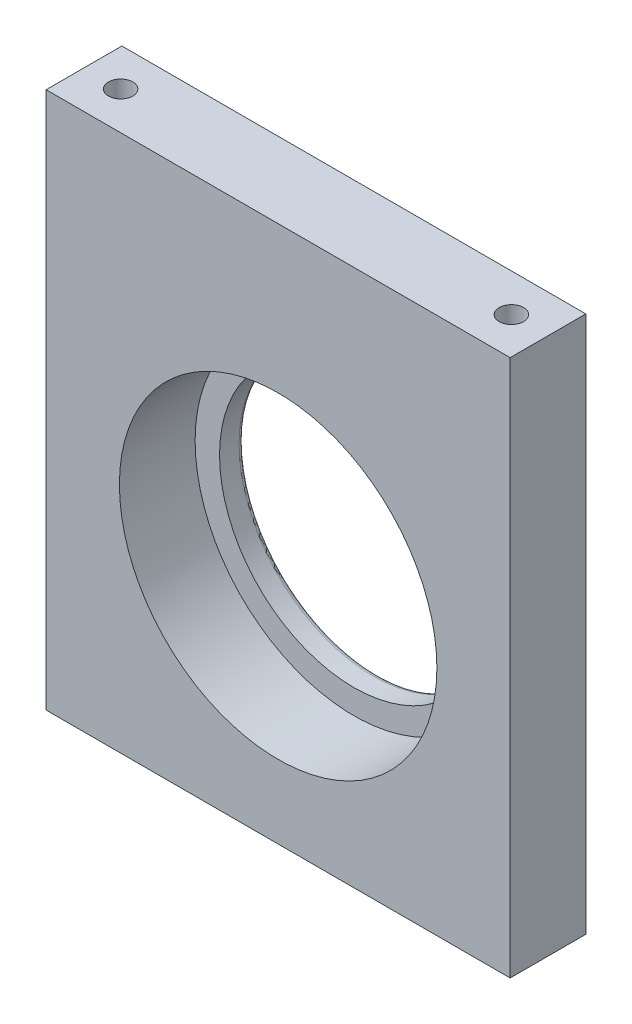
SolidWorks part; units mm, degrees
ref_plane "Plan de face" through (0, 0, 0) normal (0, 0, 1) x (1, 0, 0)
ref_plane "Plan de dessus" through (0, 0, 0) normal (0, 1, 0) x (1, 0, 0)
ref_plane "Plan de droite" through (0, 0, 0) normal (1, 0, 0) x (0, 0, -1)
sketch "Esquisse1" plane through (0, 0, 0) normal (0, 0, 1) x (1, 0, 0)
  line L0 (-95, 0) -> (95, 0)
  line L1 (95, 0) -> (95, 220)
  line L2 (95, 220) -> (-95, 220)
  line L3 (-95, 220) -> (-95, 0)
  line L4 (0, -1000) -> (0, 49000) construction
  point P4 (0, 0)
  dimension "D1" = 190
  dimension "D2" = 220
extrude "Boss.-Extru.1" add sketch "Esquisse1" against normal blind 31
sketch "Esquisse2" plane through (0, 0, 0) normal (0, 0, 1) x (1, 0, 0)
  line L0 (-95, 0) -> (95, 0) construction
  line L1 (95, 0) -> (95, 220) construction
  circle A0 centre (0, 95) radius 65
  dimension "D2" = 130
  dimension "D1" = 95
  dimension "D3" = 95
extrude "Enlèv. mat.-Extru.1" cut sketch "Esquisse2" against normal blind 38 contours A0
sketch "Esquisse3" plane through (0, 220, 0) normal (0, 1, 0) x (1, 0, 0)
  line L0 (95, 0) -> (-95, 0) construction
  line L1 (-95, 31) -> (-95, 0) construction
  circle A0 centre (-80, 15.5) radius 5
  dimension "D3" = 10
  dimension "D1" = 15.5
  dimension "D2" = 15
extrude "Enlèv. mat.-Extru.2" cut sketch "Esquisse3" against normal blind 30
mirror "Symétrie1" about plane through (0, 0, 0) normal (1, 0, 0) of "Enlèv. mat.-Extru.2"
sketch "Esquisse4" plane through (0, 0, -31) normal (0, 0, -1) x (-1, 0, 0)
  line L1 (-75, 20) -> (75, 20)
  line L2 (-75, 20) -> (-75, 170)
  line L3 (-75, 170) -> (75, 170)
  line L4 (75, 20) -> (75, 170)
  line L5 (-75, 20) -> (75, 170) construction
  line L6 (-75, 170) -> (75, 20) construction
  circle A1 centre (0, 95) radius 55
  dimension "D1" = 110
  dimension "D2" = 150
  dimension "D3" = 150
extrude "Boss.-Extru.2" add sketch "Esquisse4" along normal blind 10
fillet "Congé1" radius 2 4 edges at (-75, 95, -31) (0, 20, -31) (75, 95, -31) (0, 170, -31)
fillet "Congé2" radius 2 1 edges at (-55, 95, -41)
equation "\"D1@Esquisse3\"=31/2"
